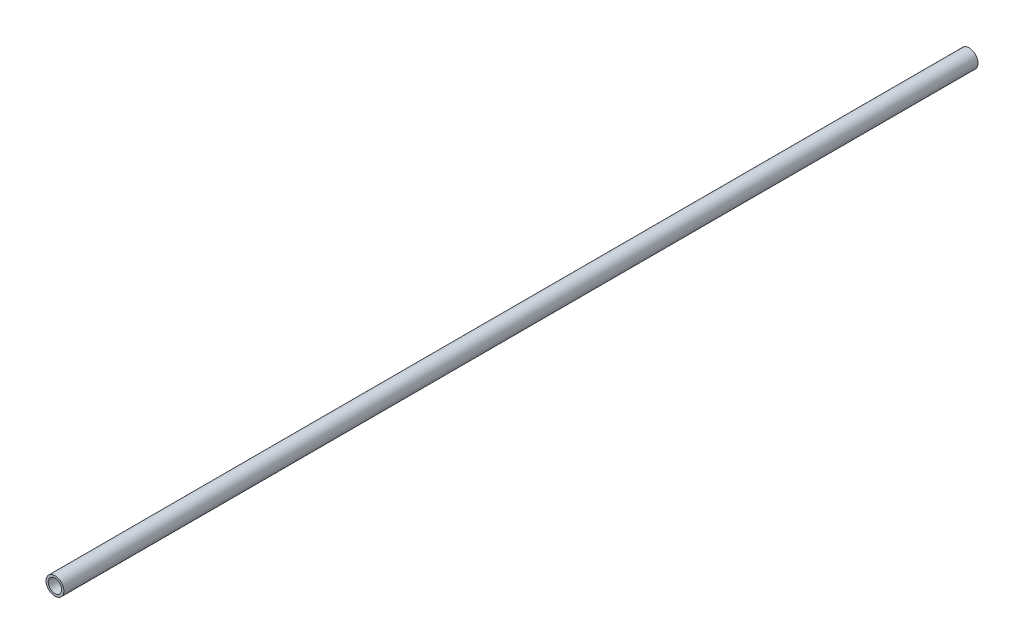
SolidWorks part; units mm, degrees
ref_plane "Plan de face" through (0, 0, 0) normal (0, 0, 1) x (1, 0, 0)
ref_plane "Plan de dessus" through (0, 0, 0) normal (0, 1, 0) x (1, 0, 0)
ref_plane "Plan de droite" through (0, 0, 0) normal (1, 0, 0) x (0, 0, -1)
sketch "Esquisse1" plane through (0, 0, 0) normal (0, 0, 1) x (1, 0, 0)
  circle A0 centre (0.7538, 0) radius 2
extrude "Extru.-Mince1" add sketch "Esquisse1" along normal blind 205 thin thin type one direction reverse wall 0.5
